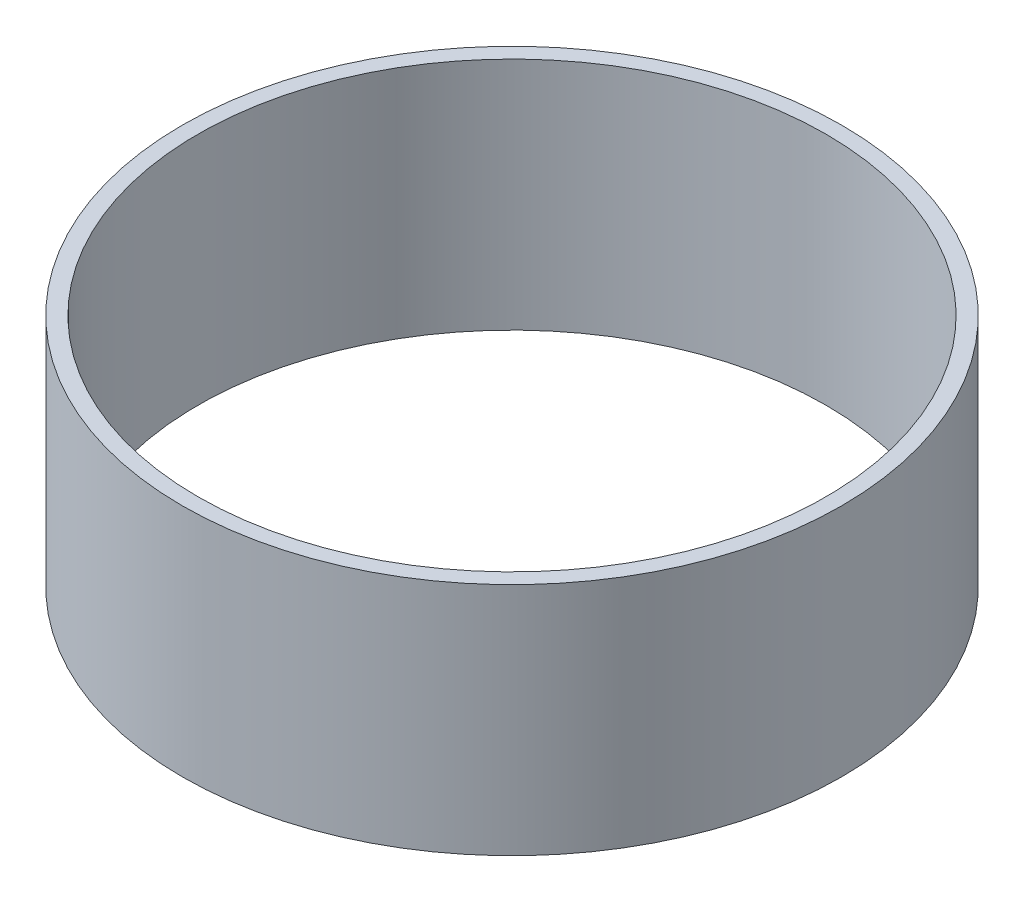
SolidWorks part; units mm, degrees
ref_plane "Front Plane" through (0, 0, 0) normal (0, 0, 1) x (1, 0, 0)
ref_plane "Top Plane" through (0, 0, 0) normal (0, 1, 0) x (1, 0, 0)
ref_plane "Right Plane" through (0, 0, 0) normal (1, 0, 0) x (0, 0, -1)
sketch "Sketch3" plane through (0, 0, 0) normal (0, 1, 0) x (1, 0, 0)
  circle A0 centre (0, 0) radius 20.066
  circle A1 centre (0, 0) radius 21.066
  dimension "D1" = 1
  dimension "D2" = 40.132
extrude "Boss-Extrude2" add sketch "Sketch3" along normal blind 15
